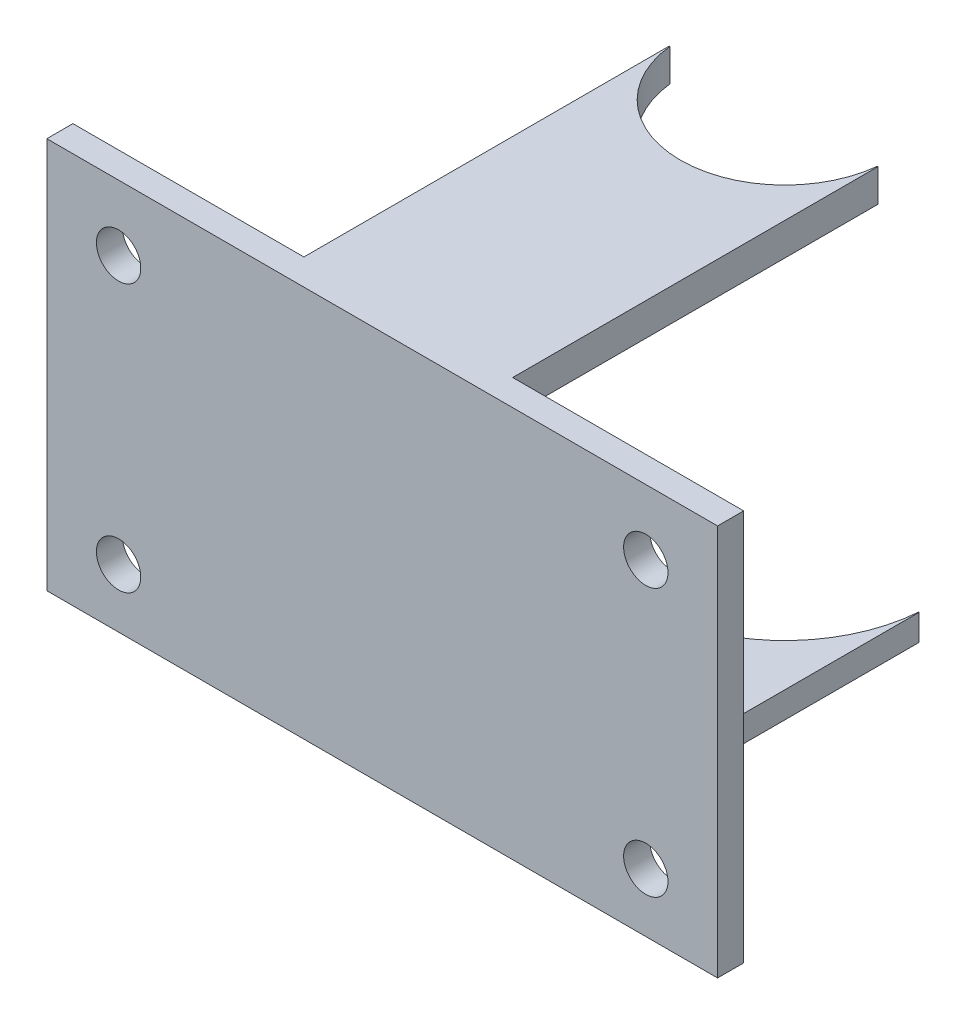
SolidWorks part; units mm, degrees
ref_plane "Front Plane" through (0, 0, 0) normal (0, 0, 1) x (1, 0, 0)
ref_plane "Top Plane" through (0, 0, 0) normal (0, 1, 0) x (1, 0, 0)
ref_plane "Right Plane" through (0, 0, 0) normal (1, 0, 0) x (0, 0, -1)
sketch "Sketch1" plane through (0, 0, 0) normal (0, 0, 1) x (1, 0, 0)
  line L1 (0, 0) -> (51.4, 0)
  line L2 (0, 0) -> (0, 30)
  line L3 (0, 30) -> (51.4, 30)
  line L4 (51.4, 0) -> (51.4, 30)
  dimension "D1" = 51.4
  dimension "D2" = 30
extrude "Boss-Extrude1" add sketch "Sketch1" along normal blind 2
sketch "Sketch2" plane through (0, 0, 0) normal (0, 0, -1) x (-1, 0, 0)
  line L0 (-51.4, 0) -> (-51.4, 30) construction
  line L1 (-5.5, 25) -> (-45.9, 25) construction
  line L2 (-5.5, 25) -> (-5.5, 4.5) construction
  line L3 (-5.5, 4.5) -> (-45.9, 4.5) construction
  line L4 (-45.9, 25) -> (-45.9, 4.5) construction
  line L5 (-5.5, 25) -> (-45.9, 4.5) construction
  line L6 (-5.5, 4.5) -> (-45.9, 25) construction
  line L7 (0, 30) -> (0, 0) construction
  line L8 (-51.4, 30) -> (0, 30) construction
  circle A0 centre (-45.9, 25) radius 1.7
  circle A1 centre (-5.5, 25) radius 1.7
  circle A2 centre (-5.5, 4.5) radius 1.7
  circle A3 centre (-45.9, 4.5) radius 1.7
  point P9 (-25.7, 14.75)
  dimension "D1" = 3.4
  dimension "D2" = 5.5
  dimension "D3" = 5.5
  dimension "D4" = 5
  dimension "D5" = 20.5
extrude "Cut-Extrude1" cut sketch "Sketch2" against normal blind 15
sketch "Sketch3" plane through (0, 0, 0) normal (0, 0, -1) x (-1, 0, 0)
  line L5 (-25.7, 30) -> (-25.7, 0) construction
  line L6 (-51.4, 30) -> (0, 30) construction
  line L12 (0, 0) -> (-51.4, 0) construction
  line L14 (-33.7, 27.5) -> (-17.7, 27.5)
  line L15 (-33.7, 27.5) -> (-33.7, 30)
  line L16 (-33.7, 30) -> (-17.7, 30)
  line L17 (-17.7, 27.5) -> (-17.7, 30)
  line L18 (-33.7, 27.5) -> (-17.7, 30) construction
  line L19 (-33.7, 30) -> (-17.7, 27.5) construction
  line L20 (-36.85, 2) -> (-14.55, 2)
  line L21 (-36.85, 2) -> (-36.85, 0)
  line L22 (-36.85, 0) -> (-14.55, 0)
  line L23 (-14.55, 2) -> (-14.55, 0)
  line L24 (-36.85, 2) -> (-14.55, 0) construction
  line L25 (-36.85, 0) -> (-14.55, 2) construction
  point P10 (-25.7, 28.75)
  point P15 (-25.7, 1)
  dimension "D1" = 16
  dimension "D2" = 2.5
  dimension "D3" = 22.3
  dimension "D4" = 2
extrude "Boss-Extrude2" add sketch "Sketch3" along normal blind 28
sketch "Sketch4" plane through (0, 30, 0) normal (0, 1, 0) x (1, 0, 0)
  line L0 (51.4, 0) -> (33.7, 0) construction
  line L1 (25.7, 28.85) -> (25.7, -2) construction
  line L3 (51.4, -2) -> (0, -2) construction
  circle A0 centre (25.7, 28.85) radius 8
  dimension "D1" = 16
  dimension "D2" = 28.85
extrude "Cut-Extrude3" cut sketch "Sketch4" against normal blind 10
sketch "Sketch6" plane through (0, 2, 0) normal (0, 1, 0) x (1, 0, 0)
  circle A0 centre (25.7, 28.85) radius 11.15
  dimension "D1" = 22.3
extrude "Cut-Extrude4" cut sketch "Sketch6" against normal blind 10
